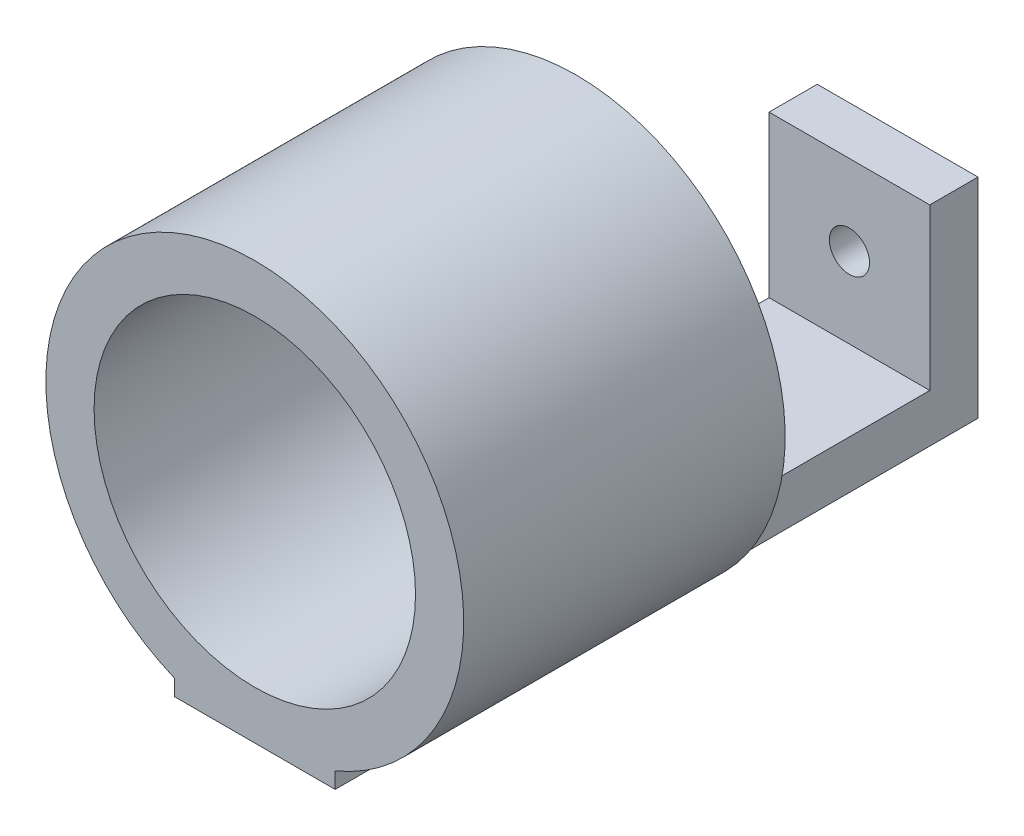
SolidWorks part; units mm, degrees
ref_plane "Front Plane" through (0, 0, 0) normal (0, 0, 1) x (1, 0, 0)
ref_plane "Top Plane" through (0, 0, 0) normal (0, 1, 0) x (1, 0, 0)
ref_plane "Right Plane" through (0, 0, 0) normal (1, 0, 0) x (0, 0, -1)
sketch "Sketch1" plane through (0, 0, 0) normal (0, 1, 0) x (1, 0, 0)
  line L1 (0, 0) -> (12.7, 0)
  line L2 (0, 0) -> (0, 50.8)
  line L3 (0, 50.8) -> (12.7, 50.8)
  line L4 (12.7, 0) -> (12.7, 50.8)
  dimension "D1" = 50.8
  dimension "D2" = 12.7
extrude "Boss-Extrude1" add sketch "Sketch1" along normal blind 3.81
sketch "Sketch2" plane through (0, 0, 0) normal (0, 0, 1) x (1, 0, 0)
  line L1 (0, 0) -> (12.7, 0) construction
  circle A0 centre (6.35, 16.51) radius 16.51
  circle A1 centre (6.35, 16.51) radius 12.7
  point P5 (0, 0)
  point P7 (0, 0)
  point P8 (6.35, 0)
  point P9 (0, 0)
  dimension "D1" = 25.4
  dimension "D2" = 3.81
extrude "Boss-Extrude2" add sketch "Sketch2" against normal blind 25.4
sketch "Sketch3" plane through (0, 0, -50.8) normal (0, 0, -1) x (-1, 0, 0)
  line L0 (0, 3.81) -> (0, 0) construction
  line L1 (-12.7, 3.81) -> (0, 3.81)
  line L2 (-12.7, 3.81) -> (-12.7, 16.51)
  line L3 (-12.7, 16.51) -> (0, 16.51)
  line L4 (0, 3.81) -> (0, 16.51)
  circle A0 centre (-6.35, 10.16) radius 1.5875
  point P9 (0, 0)
  point P10 (0, 10.16)
  point P11 (0, 0)
  point P12 (-6.35, 16.51)
  dimension "D2" = 3.175
  dimension "D1" = 12.7
extrude "Boss-Extrude3" add sketch "Sketch3" against normal blind 3.81 contours L3 L4 L1 L2 | A0
